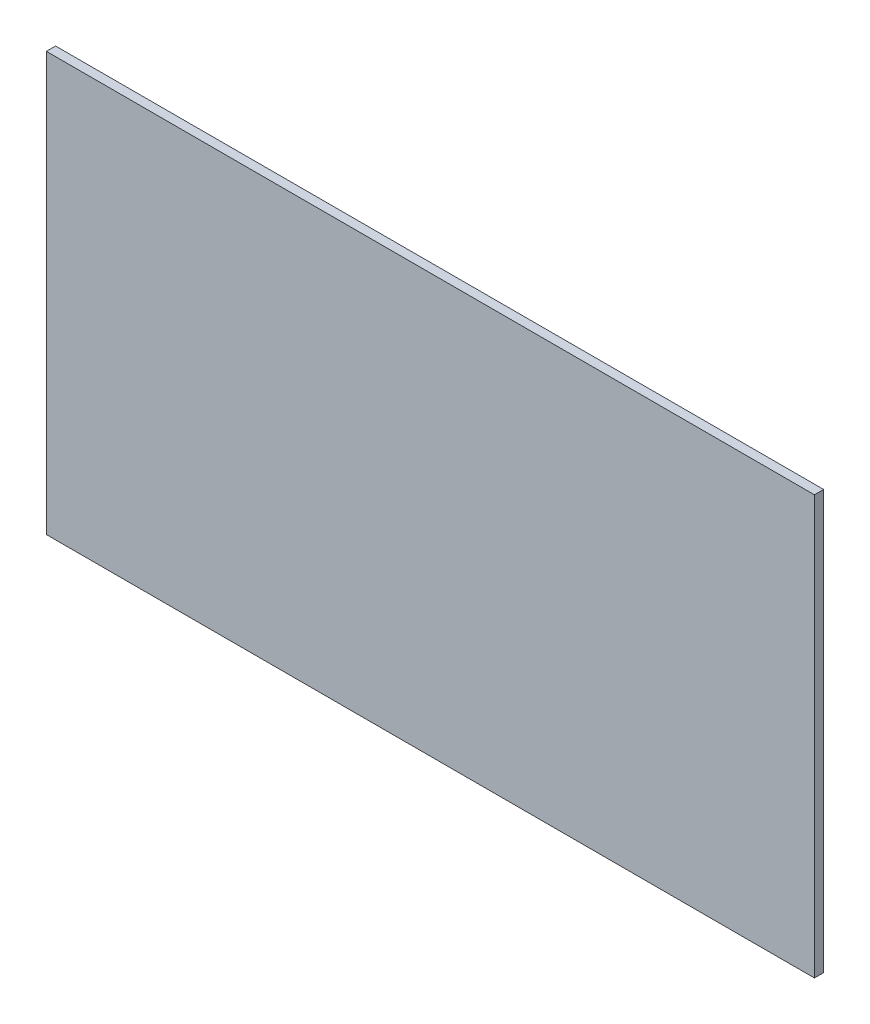
SolidWorks part; units mm, degrees
ref_plane "Front Plane" through (0, 0, 0) normal (0, 0, 1) x (1, 0, 0)
ref_plane "Top Plane" through (0, 0, 0) normal (0, 1, 0) x (1, 0, 0)
ref_plane "Right Plane" through (0, 0, 0) normal (1, 0, 0) x (0, 0, -1)
sketch "Sketch1" plane through (0, 0, 0) normal (0, 0, 1) x (1, 0, 0)
  line L1 (0, 0) -> (140, 0)
  line L2 (0, 0) -> (0, 76.28)
  line L3 (0, 76.28) -> (140, 76.28)
  line L4 (140, 0) -> (140, 76.28)
  dimension "D1" = 76.28
  dimension "D2" = 140
extrude "Boss-Extrude1" add sketch "Sketch1" along normal blind 1.68
